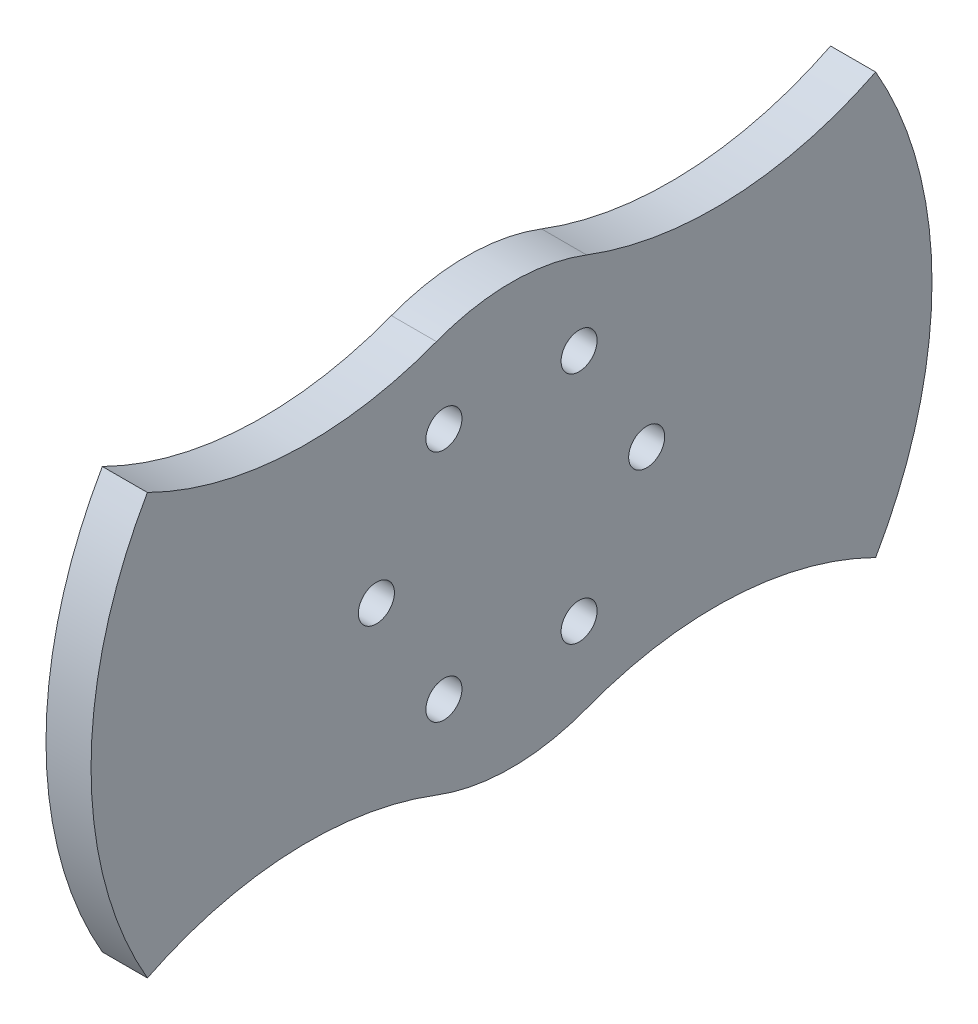
SolidWorks part; units mm, degrees
material "AISI 1020"
ref_plane "Front Plane" through (0, 0, 0) normal (0, 0, 1) x (1, 0, 0)
ref_plane "Top Plane" through (0, 0, 0) normal (0, 1, 0) x (1, 0, 0)
ref_plane "Right Plane" through (0, 0, 0) normal (1, 0, 0) x (0, 0, -1)
sketch "Sketch1" plane through (0, 0, 0) normal (1, 0, 0) x (0, 0, -1)
  circle A0 centre (0, 0) radius 44.45
  dimension "D1" = 88.9
extrude "Boss-Extrude1" add sketch "Sketch1" along normal mid plane 4.7625
sketch "Sketch2" plane through (2.3813, 0, 0) normal (1, 0, 0) x (0, 0, -1)
  line L0 (-38.4948, 22.225) -> (-38.4948, -22.225) construction
  line L1 (38.4948, 22.225) -> (38.4948, -22.225) construction
  arc A0 (-7.9374, -20.7593) -> (7.9374, -20.7593) centre (0, 0) ccw
  circle A1 centre (0, 0) radius 44.45 construction
  arc A2 (-38.4948, 22.225) -> (-7.9374, 20.7593) centre (-21.5443, 56.3467) ccw
  arc A3 (-7.9374, -20.7593) -> (-38.4948, -22.225) centre (-21.5443, -56.3467) ccw
  arc A4 (38.4948, -22.225) -> (7.9374, -20.7593) centre (21.5443, -56.3467) ccw
  arc A5 (7.9374, 20.7593) -> (38.4948, 22.225) centre (21.5443, 56.3467) ccw
  arc A6 (7.9374, 20.7593) -> (-7.9374, 20.7593) centre (0, 0) ccw
  arc A7 (-38.4948, -22.225) -> (38.4948, -22.225) centre (0, 0) ccw
  arc A8 (38.4948, 22.225) -> (-38.4948, 22.225) centre (0, 0) ccw
  dimension "D1" = 44.45
  dimension "D3" = 76.2
  dimension "D2" = 44.45
extrude "Cut-Extrude1" cut sketch "Sketch2" against normal through all
sketch "Sketch3" plane through (2.3813, 0, 0) normal (1, 0, 0) x (0, 0, -1)
  circle A0 centre (0, 0) radius 14.2875 construction
  circle A1 centre (-14.2875, 0) radius 1.905
  circle A2 centre (-7.1438, 12.3733) radius 1.905
  circle A3 centre (7.1437, 12.3733) radius 1.905
  circle A4 centre (14.2875, 0) radius 1.905
  circle A5 centre (7.1438, -12.3733) radius 1.905
  circle A6 centre (-7.1437, -12.3733) radius 1.905
  point P18 (0, 0)
  dimension "D1" = 28.575
  dimension "D2" = 3.81
  dimension "D3" = 6
extrude "Mounting holes" cut sketch "Sketch3" against normal through all
sketch "Sketch4" plane through (2.3813, 0, 0) normal (1, 0, 0) x (0, 0, -1)
  circle A0 centre (0, 0) radius 14.7066 construction
  circle A1 centre (0, 14.7066) radius 3.429
  circle A2 centre (12.7363, 7.3533) radius 3.429
  circle A3 centre (12.7363, -7.3533) radius 3.429
  circle A4 centre (0, -14.7066) radius 3.429
  circle A5 centre (-12.7363, -7.3533) radius 3.429
  circle A6 centre (-12.7363, 7.3533) radius 3.429
  point P18 (0, 0)
  dimension "D1" = 29.4132
  dimension "D2" = 6.858
  dimension "D3" = 6
sketch "Sketch6" plane through (2.3813, 0, 0) normal (1, 0, 0) x (0, 0, -1)
  circle A0 centre (0, 0) radius 9.525
  dimension "D1" = 19.05
extrude "Cut-Extrude3" [suppressed] cut sketch "Sketch6" against normal through all
sketch "Sketch7" plane through (0, 0, 0) normal (0, 1, 0) x (1, 0, 0)
  line L0 (-2.3813, -7.9374) -> (-2.3813, -38.4948) construction
  line L1 (2.3813, -38.4948) -> (2.3813, -7.9374) construction
  line L2 (-2.3813, -30.8748) -> (-2.3813, -38.4948)
  line L3 (2.3813, -38.4948) -> (2.3813, -30.8748)
  line L4 (-2.3813, -30.8748) -> (2.3813, -30.8748)
  line L5 (-2.3813, -38.4948) -> (2.3813, -38.4948) construction
  line L6 (-2.3813, -38.4948) -> (2.3813, -38.4948)
  dimension "D1" = 7.62
extrude "Boss-Extrude2" [suppressed] add sketch "Sketch7" against normal up to vertex
fillet "Fillet1" [suppressed] radius 2.54
equation "\"1.75x2\"=5.46605"
